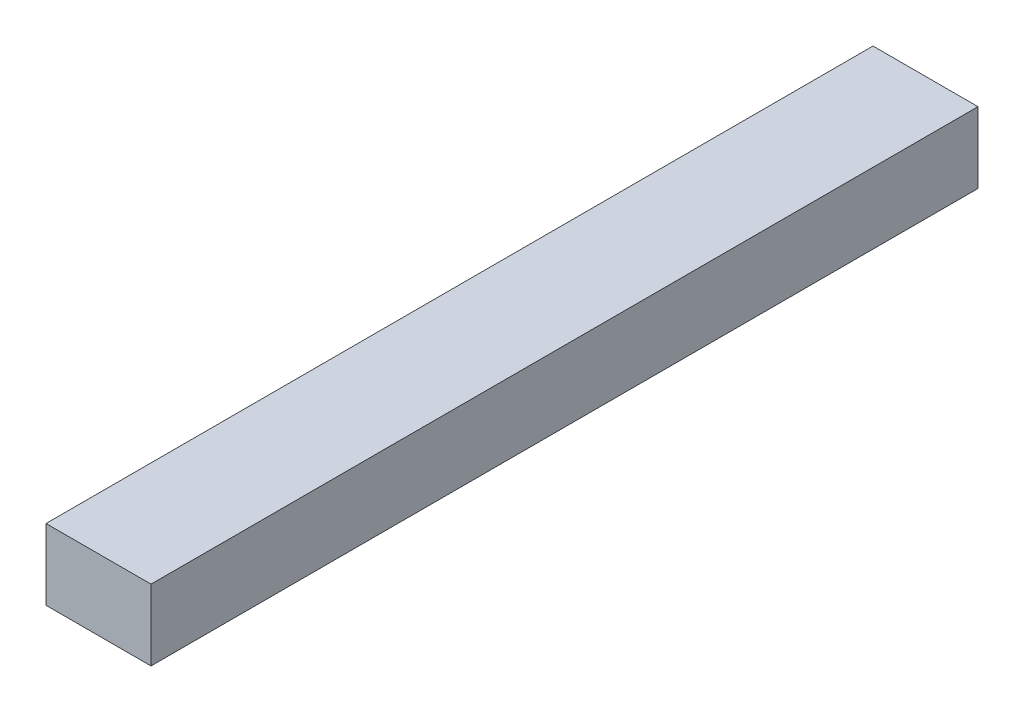
SolidWorks part; units mm, degrees
ref_plane "Front Plane" through (0, 0, 0) normal (0, 0, 1) x (1, 0, 0)
ref_plane "Top Plane" through (0, 0, 0) normal (0, 1, 0) x (1, 0, 0)
ref_plane "Right Plane" through (0, 0, 0) normal (1, 0, 0) x (0, 0, -1)
sketch "Sketch1" plane through (0, -30, 0) normal (0, -1, 0) x (1, 0, 0)
  line L1 (60, 60) -> (76, 60)
  line L2 (60, 60) -> (60, -66)
  line L3 (60, -66) -> (76, -66)
  line L4 (76, 12) -> (60, 12)
  line L5 (60, 12) -> (60, -36)
  line L6 (60, -36) -> (76, -36)
  line L7 (76, -36) -> (76, 12)
  line L8 (76, 12) -> (60, 12) construction
  line L9 (60, 12) -> (60, -36) construction
  line L10 (60, -36) -> (76, -36) construction
  line L11 (76, -36) -> (76, 12) construction
  line L12 (76, 60) -> (76, -66)
  dimension "D2" = 30
  dimension "D3" = 48
  dimension "D1" = 0
extrude "Boss-Extrude1" add sketch "Sketch1" against normal up to surface (10.8 mm away)
